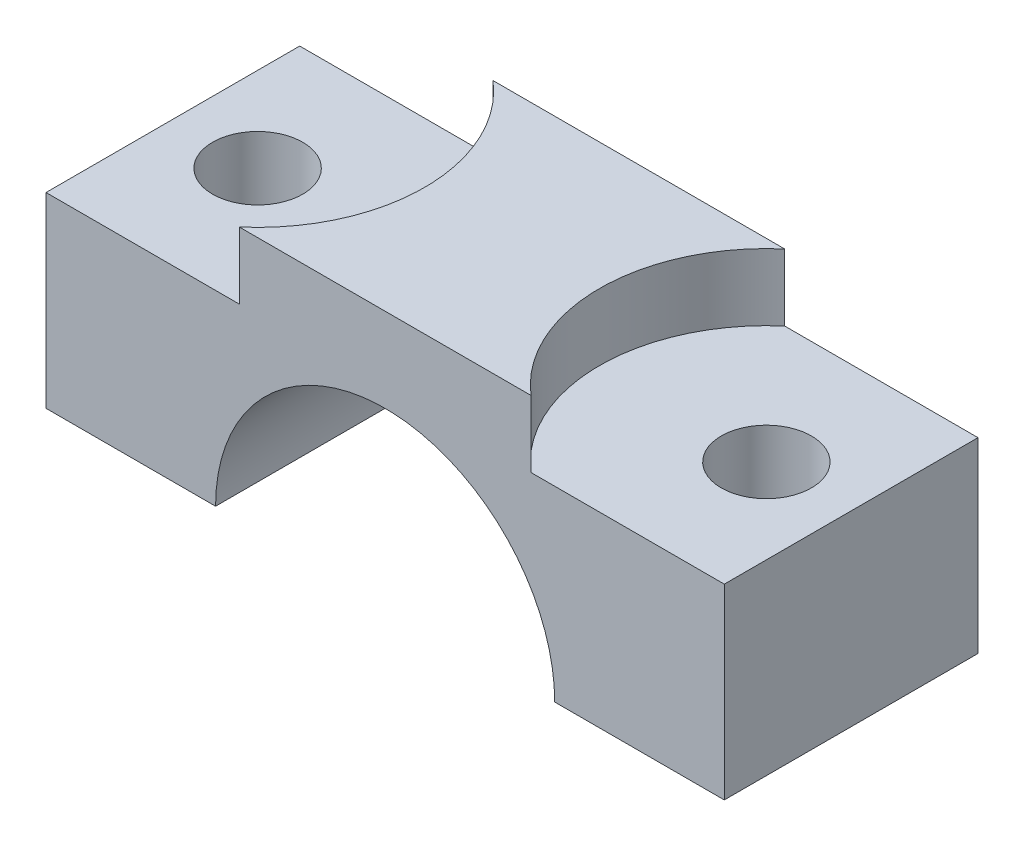
SolidWorks part; units mm, degrees
ref_plane "Front Plane" through (0, 0, 0) normal (0, 0, 1) x (1, 0, 0)
ref_plane "Top Plane" through (0, 0, 0) normal (0, 1, 0) x (1, 0, 0)
ref_plane "Right Plane" through (0, 0, 0) normal (1, 0, 0) x (0, 0, -1)
sketch "Sketch1" plane through (0, 0, 0) normal (0, 0, 1) x (1, 0, 0)
  line L1 (-25.4, 9.5) -> (25.4, 9.5)
  line L2 (-25.4, 9.5) -> (-25.4, -9.5)
  line L3 (-25.4, -9.5) -> (25.4, -9.5)
  line L4 (25.4, 9.5) -> (25.4, -9.5)
  line L5 (-25.4, 9.5) -> (25.4, -9.5) construction
  line L6 (-25.4, -9.5) -> (25.4, 9.5) construction
  circle A0 centre (0, -9.5) radius 12.7
  point P0 (0, 0)
  dimension "D3" = 25.4
  dimension "D1" = 50.8
  dimension "D2" = 19
extrude "Boss-Extrude1" add sketch "Sketch1" along normal mid plane 19 contours A0 L3 L4 L1 L2
sketch "Sketch2" plane through (0, -9.5, 0) normal (0, -1, 0) x (1, 0, 0)
  line L0 (-25.4, 0) -> (-12.7, 0) construction
  line L1 (-25.4, 9.5) -> (-25.4, -9.5) construction
  line L2 (-12.7, 9.5) -> (-12.7, -9.5) construction
  line L3 (12.7, 0) -> (25.4, 0) construction
  line L4 (12.7, 9.5) -> (12.7, -9.5) construction
  line L5 (25.4, 9.5) -> (25.4, -9.5) construction
  point P12 (-19.05, 0)
  point P13 (19.05, 0)
hole_wizard "CBORE for M12 Hex Head Cap Screw1" positions "3DSketch2" profile "Sketch5" counterbore size "M12" standard "ISO"
sketch3d "3DSketch2"
  point P0 (19.05, 9.5, 0)
  point P2 (-19.05, 9.5, 0)
  point P5 (0, 0, 0)
sketch "Sketch5" plane through (19.05, 9.5, 0) normal (1, 0, 0) x (0, 0, 1)
  line L0 (0, 0) -> (0, 327.3079)
  line L1 (0, 327.3079) -> (3.375, 325.28)
  line L2 (3.375, 325.28) -> (3.375, 5)
  line L3 (3.375, 5) -> (12.5, 5)
  line L4 (12.5, 5) -> (12.5, 0)
  line L5 (12.5, 0) -> (0, 0)
  line L10 (0, 327.3079) -> (-3.375, 325.28) construction
  line L11 (0, -6.35) -> (0, 107.95) construction
  dimension "Hole Dia." = 6.75
  dimension "Hole Depth" = 325.28
  dimension "C'Bore Dia." = 25
  dimension "C'Bore Depth" = 5
  dimension "Drill Angle" = 118
